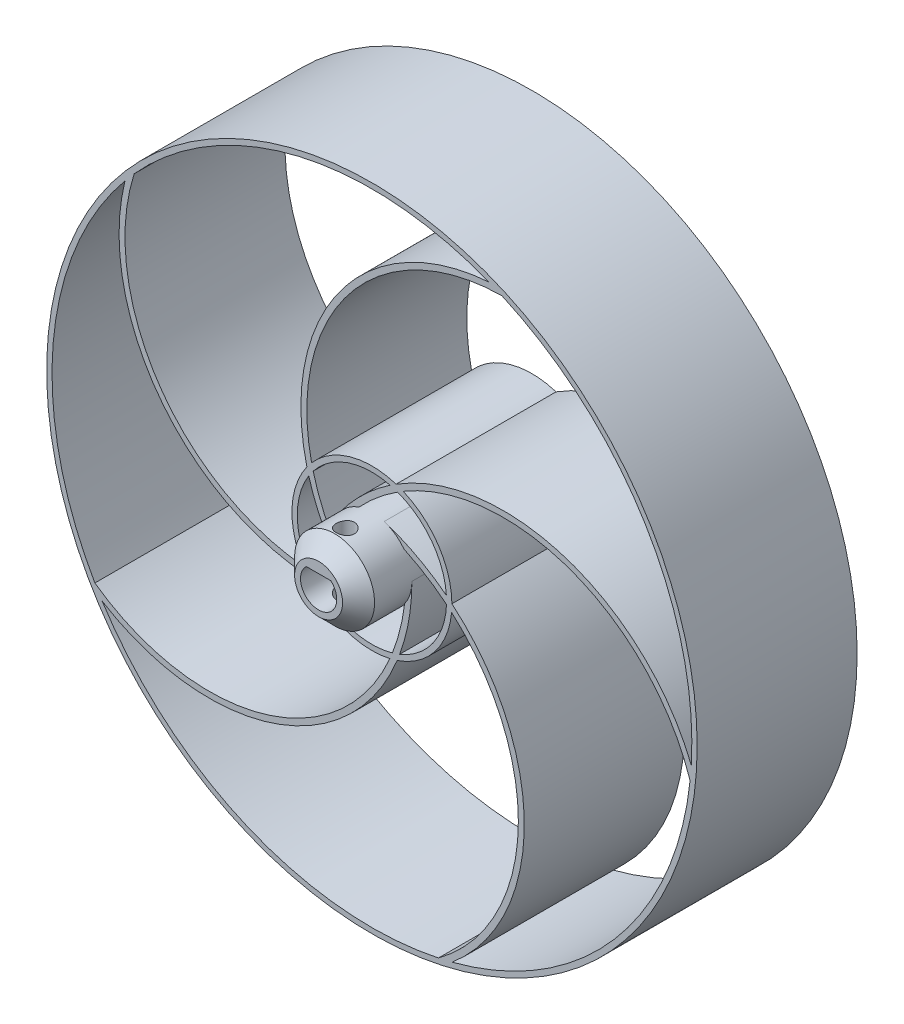
SolidWorks part; units mm, degrees
ref_plane "Front Plane" through (0, 0, 0) normal (0, 0, 1) x (1, 0, 0)
ref_plane "Top Plane" through (0, 0, 0) normal (0, 1, 0) x (1, 0, 0)
ref_plane "Right Plane" through (0, 0, 0) normal (1, 0, 0) x (0, 0, -1)
sketch "Sketch1" plane through (0, 0, 0) normal (0, 0, 1) x (1, 0, 0)
  line L0 (0, 0) -> (-30.5, 0) construction
  line L1 (-1.1522, 1.25) -> (1.1522, 1.25)
  circle A0 centre (0, 0) radius 30.5
  circle A1 centre (0, 0) radius 30
  circle A2 centre (0, 0) radius 3.75
  arc A3 (3.75, 0) -> (-25.2971, -16.1262) centre (-15.25, 0) cw
  arc A4 (3.0667, -2.1581) -> (-25.9804, -15.0007) centre (-15.25, 0) cw
  arc A5 (-1.1048, -3.5836) -> (-22.2949, 20.0734) centre (-4.7125, 14.5036) cw
  arc A6 (1.1588, -3.5665) -> (-23.1542, 19.0757) centre (-4.7125, 14.5036) cw
  arc A7 (-3.7496, -0.0566) -> (12.2014, 27.4067) centre (12.3375, 8.9637) cw
  arc A8 (-3.0338, -2.2042) -> (10.9871, 27.9157) centre (12.3375, 8.9637) cw
  arc A9 (-1.2125, 3.5486) -> (29.8357, -3.1351) centre (12.3375, -8.9637) cw
  arc A10 (-3.0338, 2.2042) -> (29.9446, -1.8229) centre (12.3375, -8.9637) cw
  arc A11 (3.0002, 2.2497) -> (6.2381, -29.3443) centre (-4.7125, -14.5036) cw
  arc A12 (1.1588, 3.5665) -> (7.5197, -29.0423) centre (-4.7125, -14.5036) cw
  arc A13 (1.1522, 1.25) -> (-1.1522, 1.25) centre (0, 0) cw
  point P10 (-15.25, 0)
  dimension "D1" = 61
  dimension "D2" = 0.5
  dimension "D3" = 7.5
  dimension "D4" = 0.5566
  dimension "D7" = 1.7
  dimension "D6" = 1.25
  dimension "D5" = 5
extrude "Boss-Extrude1" add sketch "Sketch1" along normal blind 15
sketch "Sketch2" plane through (0, 0, 15) normal (0, 0, 1) x (1, 0, 0)
  line L2 (-1.1522, 1.25) -> (1.1522, 1.25) construction
  line L3 (-1.1522, 1.25) -> (1.1522, 1.25)
  circle A0 centre (0, 0) radius 3.75
  arc A3 (-1.1522, 1.25) -> (1.1522, 1.25) centre (0, 0) ccw construction
  arc A4 (-1.1522, 1.25) -> (1.1522, 1.25) centre (0, 0) ccw
  dimension "D1" = 7.5
extrude "Boss-Extrude2" add sketch "Sketch2" along normal blind 5
sketch "Sketch3" plane through (0, 1.25, 0) normal (0, -1, 0) x (1, 0, 0)
  line L0 (1.1522, 20) -> (0, 17.5) construction
  line L1 (0, 17.5) -> (-1.1522, 20) construction
  line L3 (1.1522, 20) -> (-1.1522, 20) construction
  circle A0 centre (0, 17.5) radius 0.85
  dimension "D2" = 1.7
  dimension "D1" = 2.5
extrude "Cut-Extrude1" cut sketch "Sketch3" against normal through all and the other way through all contours A0
chamfer "Chamfer1" distance 1.5 angle 45 1 edges at (3.75, 0, 20)
sketch "Sketch4" plane through (0, 0, 0) normal (0, 0, -1) x (-1, 0, 0)
  circle A0 centre (0, 0) radius 7
  circle A1 centre (0, 0) radius 7.5
  dimension "D1" = 0.5
  dimension "D2" = 15
extrude "Boss-Extrude3" add sketch "Sketch4" against normal up to surface (15 mm away) up to face at (0, 0, 15)
